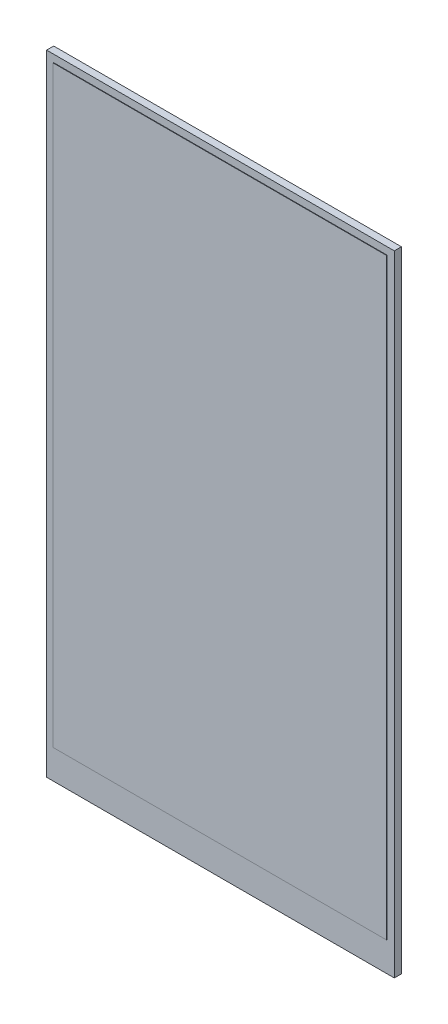
SolidWorks part; units mm, degrees
material "1.4000 (X6Cr13)"
ref_plane "Plan de face" through (0, 0, 0) normal (0, 0, 1) x (1, 0, 0)
ref_plane "Plan de dessus" through (0, 0, 0) normal (0, 1, 0) x (1, 0, 0)
ref_plane "Plan de droite" through (0, 0, 0) normal (1, 0, 0) x (0, 0, -1)
sketch "Esquisse1" plane through (0, 0, 0) normal (0, 0, 1) x (1, 0, 0)
  line L1 (0, 0) -> (70.94, 0)
  line L2 (0, 0) -> (0, 128.49)
  line L3 (0, 128.49) -> (70.94, 128.49)
  line L4 (70.94, 0) -> (70.94, 128.49)
  dimension "D1" = 128.49
  dimension "D2" = 70.94
extrude "Boss.-Extru.1" add sketch "Esquisse1" along normal blind 1.45
sketch "Esquisse2" plane through (0, 0, 1.45) normal (0, 0, 1) x (1, 0, 0)
  line L0 (0, 128.49) -> (70.94, 128.49) construction
  line L1 (35.47, 128.49) -> (35.47, 6.03) construction
  line L2 (35.47, 6.03) -> (69.49, 6.03) construction
  line L4 (69.49, 6.03) -> (1.45, 6.03)
  line L5 (69.49, 6.03) -> (69.49, 126.99)
  line L6 (69.49, 126.99) -> (1.45, 126.99)
  line L7 (1.45, 6.03) -> (1.45, 126.99)
  dimension "D1" = 122.46
  dimension "D2" = 34.02
  dimension "D3" = 120.96
  dimension "D4" = 68.04
extrude "Boss.-Extru.2" add sketch "Esquisse2" along normal blind 0.1
